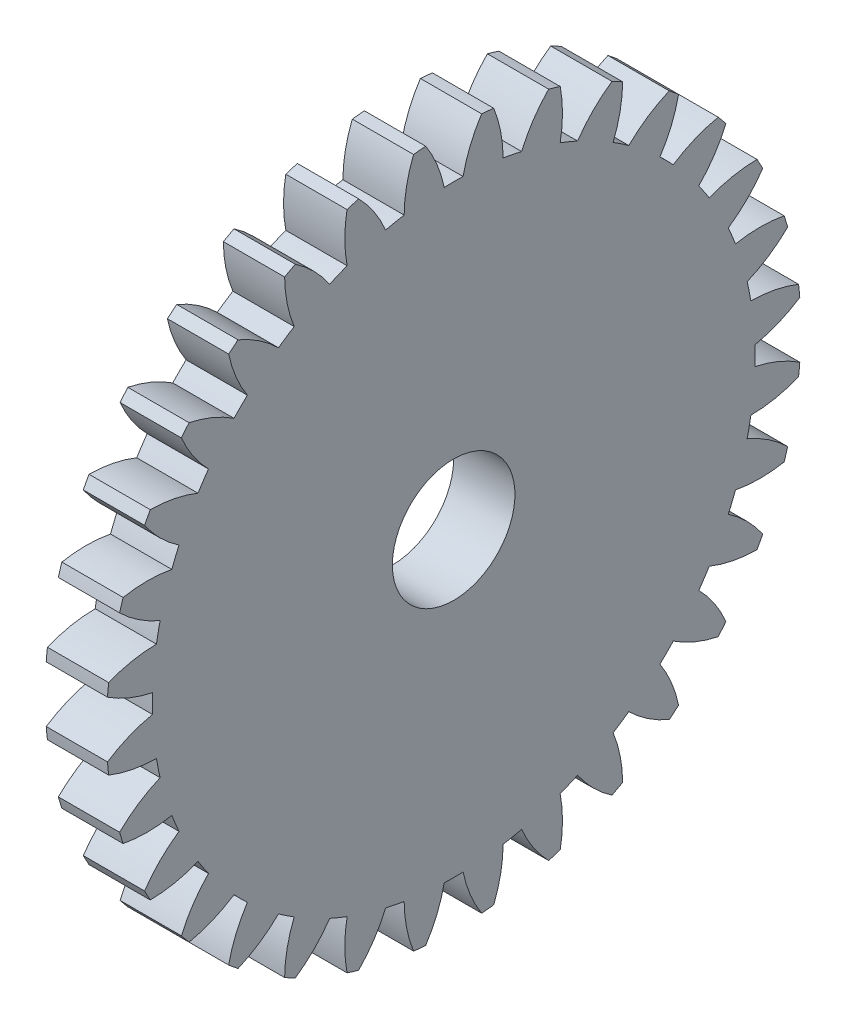
SolidWorks part; units mm, degrees
ref_plane "Plane1" through (0, 0, 0) normal (0, 0, 1) x (1, 0, 0)
ref_plane "Plane2" through (0, 0, 0) normal (0, 1, 0) x (1, 0, 0)
ref_plane "Plane3" through (0, 0, 0) normal (1, 0, 0) x (0, 0, -1)
other "Configuration Table"
sketch "HoldingSke" plane through (0, 0, 0) normal (0, 1, 0) x (1, 0, 0)
  line L0 (0, 0) -> (0.848, -0.5299)
  line L1 (-15, 0) -> (100, 0) construction
  line L2 (0, 0) -> (-2.1039, 2.3779)
  line L3 (0, 0) -> (-11.863, 4.5341)
  line L4 (0, 0) -> (7.3237, 4.5764)
  line L5 (0, 0) -> (-46.8476, -17.4728)
  line L6 (0, 0) -> (-2.4869, -1.6779)
  line L7 (-2.1039, 2.3779) -> (8.6586, 51.2059)
  line L8 (-76.2, 54.61) -> (-75.2, 54.61)
  line L9 (-71.009, 38.7566) -> (-53.1078, 45.2721)
  line L10 (-76.2, 71.12) -> (104.1128, 71.12)
  line L11 (0, 0) -> (-3, 0)
  line L12 (-76.2, 101.6) -> (-76.162, 101.6)
  line L13 (24.9733, 27.94) -> (52.9518, 28.4284)
  line L14 (24.9733, 27.94) -> (24.9743, 27.94)
  line L15 (24.9733, 27.94) -> (100.4006, 29.5858)
  line L16 (-63.627, -1) -> (-12.827, -1)
  circle A0 centre (0, 0) radius 3
  circle A1 centre (0, 0) radius 14.749
  circle A2 centre (0, 0) radius 37.5
  circle A3 centre (0, 0) radius 3
  dimension "MHD" = 29.498
  dimension "Hub_dia" = 75
  dimension "Bore" = 6
  dimension "MBD" = 6
  dimension "Num_teeth" = 32
  dimension "Pitch" = 1
  dimension "Overall_len" = 50
  dimension "Show_teeth" = 32
  dimension "Thickness" = 3
  dimension "OAL" = 50.0001
  dimension "T_dim" = 1
  dimension "Ap" = 20
  dimension "H" = 19.05
  dimension "Pitch_radius" = 180.3128
  dimension "Width" = 3
  dimension "Backlash" = 0.038
  dimension "Addendum_fac" = 1
  dimension "Dedendum_fac" = 1.25
  dimension "Clearance_fac" = 0.25
  dimension "Dedendum_add" = 0.001
  dimension "Module" = 1
sketch "BasProSke" plane through (0, 0, 0) normal (0, 1, 0) x (1, 0, 0)
  line L0 (-10, 0) -> (60, 0) construction
  line L1 (0, 0) -> (0, 17)
  line L2 (0, 0) -> (3, 0)
  line L3 (3, 0) -> (3, 17)
  line L4 (3, 17) -> (0, 17)
  dimension "Thickness" = 3
  dimension "Diameter" = 34
revolve "Base-Revolve" add sketch "BasProSke" angle 360 about L0
sketch "TooCutSke" plane through (0, 0, 0) normal (1, 0, 0) x (0, 0, -1)
  line L1 (0, 0) -> (0, 107) construction
  line L2 (0, 0) -> (-0.8516, 15.9773) construction
  line L3 (0, 0) -> (-3.1334, 31.8138) construction
  line L4 (-0.8516, 15.9773) -> (-1.5667, 15.9069) construction
  arc A0 (0.462, 14.7418) -> (-0.462, 14.7418) centre (0, 0) ccw
  arc A1 (1.3867, 16.9688) -> (-1.3867, 16.9688) centre (0, 0) ccw
  circle A2 centre (0, 0) radius 16 construction
  circle A3 centre (0, 0) radius 15.0351 construction
  arc A4 (-0.462, 14.7418) -> (-1.3867, 16.9688) centre (-6.7293, 13.4451) ccw
  arc A5 (1.3867, 16.9688) -> (0.462, 14.7418) centre (6.7293, 13.4451) ccw
  dimension "Root_dia" = 29.498
  dimension "Overcut_dia" = 34.0508
  dimension "Pitch_dia" = 32
  dimension "Base_dia" = 30.0702
  dimension "Flank_rad" = 6.4
  dimension "Half_ang" = 5.625
  dimension "Half_CT" = 0.7186
extrude "ToothCut" cut sketch "TooCutSke" along normal through all
fillet "Breaks" [suppressed] radius 0.02
fillet "RootFillets" [suppressed] radius 0.251
pattern_circular "TeethCuts" count 32 every 11.25 about axis through (-10, 0, 0) along (1, 0, 0) of "ToothCut", "RootFillets", "Breaks"
sketch "HubNeaOneSke" plane through (0, 0, 0) normal (-1, 0, 0) x (0, 0, 1)
  circle A0 centre (0, 0) radius 14.749
  dimension "Diameter" = 29.498
extrude "HubNearOne" [suppressed] add sketch "HubNeaOneSke" along normal blind 47.0001
sketch "HubNeaBotSke" plane through (0, 0, 0) normal (-1, 0, 0) x (0, 0, 1)
  circle A0 centre (0, 0) radius 14.749
  dimension "Diameter" = 29.498
extrude "HubNearBoth" [suppressed] add sketch "HubNeaBotSke" along normal blind 23.5
ref_plane "FarPln" through (3, 0, 0) normal (1, 0, 0) x (0, 0, -1)
sketch "HubFarSke" plane through (3, 0, 0) normal (1, 0, 0) x (0, 0, -1)
  circle A0 centre (0, 0) radius 14.749
  dimension "Diameter" = 29.498
extrude "HubFar" [suppressed] add sketch "HubFarSke" along normal blind 23.5
sketch "BorSke" plane through (0, 0, 0) normal (1, 0, 0) x (0, 0, -1)
  circle A0 centre (0, 0) radius 3
  dimension "Diameter" = 6
extrude "Bore" cut sketch "BorSke" along normal mid plane 100.0001
sketch "KeySke" plane through (0, 0, 0) normal (1, 0, 0) x (0, 0, -1)
  line L0 (-1, 0) -> (-1, 4)
  line L1 (-1, 4) -> (1, 4)
  line L2 (1, 4) -> (1, 0)
  line L3 (0, 0) -> (0, 34) construction
  line L4 (-1, 0) -> (1, 0)
  dimension "Offset" = 4
  dimension "Width" = 2
extrude "Keyway" [suppressed] cut sketch "KeySke" along normal mid plane 100.0001
pattern_circular "Keyway2" [suppressed] count 2 every 90 about axis through (-10, 0, 0) along (1, 0, 0)
equation "' \"Module@HoldingSke\" = 6.35"
equation "' \"Num_teeth@HoldingSke\" = 12"
equation "' \"Ap@HoldingSke\" =  20"
equation "' \"Ap@HoldingSke\" = 20"
equation "' \"Width@HoldingSke\" = 0.5 * 25.4"
equation "' \"Hub_dia@HoldingSke\"= 1 * 25.4"
equation "' \"Hub_dia@HoldingSke\" = 1 * 25.4"
equation "' \"Overall_len@HoldingSke\" = 1.0 * 25.4"
equation "' \"Bore@HoldingSke\" = 0.75 * 25.4"
equation "' \"T_dim@HoldingSke\" = 0.1 * 25.4"
equation "' \"Width@KeySke\" = 0.25 * 25.4"
equation "' \"Show_teeth@HoldingSke\" = 13"
equation "' \"Backlash@HoldingSke\" = 0.009 * 25.4"
equation "' \"Addendum_fac@HoldingSke\" = 1.0"
equation "' \"Dedendum_fac@HoldingSke\" = 1.25"
equation "' \"Dedendum_add@HoldingSke\" = 0.00005 * 25.4"
equation "' \"Clearance_fac@HoldingSke\" = 0.25"
equation "\"Pitch@HoldingSke\" = 1 / \"Module@HoldingSke\""
equation "\"Overcut_dia@TooCutSke\" = (\"Num_teeth@HoldingSke\" + 2 * \"Addendum_fac@HoldingSke\") / \"Pitch@HoldingSke\" + 0.002 * 25.4"
equation "\"Pitch_dia@TooCutSke\" = \"Num_teeth@HoldingSke\" / \"Pitch@HoldingSke\""
equation "\"Base_dia@TooCutSke\" = \"Num_teeth@HoldingSke\" / \"Pitch@HoldingSke\" * cos((\"Ap@HoldingSke\"  * 3.14159265 / 180))"
equation "\"Root_dia@TooCutSke\" = (\"Num_teeth@HoldingSke\" + 2) / \"Pitch@HoldingSke\" - 2 * (\"Addendum_fac@HoldingSke\" + \"Dedendum_fac@HoldingSke\") / \"Pitch@HoldingSke\" - \"Dedendum_add@HoldingSke\" * 2"
equation "\"Half_ang@TooCutSke\" = 180 / \"Num_teeth@HoldingSke\""
equation "\"Half_CT@TooCutSke\" = \"Num_teeth@HoldingSke\" / \"Pitch@HoldingSke\" * sin((3.14159265 / 2 / \"Num_teeth@HoldingSke\")) / 2 - 7 * \"Backlash@HoldingSke\" / 4"
equation "\"Flank_rad@TooCutSke\" = \"Num_teeth@HoldingSke\" / \"Pitch@HoldingSke\" / 5"
equation "\"Radius@RootFillets\" = \"Clearance_fac@HoldingSke\" / \"Pitch@HoldingSke\" + \"Dedendum_add@HoldingSke\""
equation "\"Break_rad@Breaks\" = 0.02 / \"Pitch@HoldingSke\""
equation "\"Thickness@HoldingSke\" = \"Width@HoldingSke\""
equation "\"OAL@HoldingSke\" = \"Thickness@HoldingSke\""
equation "\"MHD@HoldingSke\" = (\"Num_teeth@HoldingSke\" + 2) / \"Pitch@HoldingSke\" - 2 * (\"Addendum_fac@HoldingSke\" + \"Dedendum_fac@HoldingSke\")  / \"Pitch@HoldingSke\" - \"Dedendum_add@HoldingSke\" * 2"
equation "\"MBD@HoldingSke\" = (\"Num_teeth@HoldingSke\" + 2) / \"Pitch@HoldingSke\" - 2 * (\"Addendum_fac@HoldingSke\" + \"Dedendum_fac@HoldingSke\")  / \"Pitch@HoldingSke\" - \"Dedendum_add@HoldingSke\" * 2 - 0.002 * 25.4"
equation "\"MHD@HoldingSke\" = ((sgn( \"MHD@HoldingSke\" - \"Hub_dia@HoldingSke\" )-1)*( \"MHD@HoldingSke\" - \"Hub_dia@HoldingSke\" ))/-2+ \"Hub_dia@HoldingSke\""
equation "\"MBD@HoldingSke\" = ((sgn( \"MBD@HoldingSke\" - \"Bore@HoldingSke\" )-1)*( \"MBD@HoldingSke\" - \"Bore@HoldingSke\" ))/-2+ \"Bore@HoldingSke\""
equation "\"OAL@HoldingSke\" = ((sgn( \"OAL@HoldingSke\" - \"Overall_len@HoldingSke\" )+1)*( \"OAL@HoldingSke\" - \"Overall_len@HoldingSke\" ))/2 + \"Overall_len@HoldingSke\" + 0.000002 * 25.4"
equation "\"Num_teeth@TeethCuts\" = int( \"Show_teeth@HoldingSke\" ) + 1"
equation "\"Num_teeth@TeethCuts\" = ((sgn( \"Num_teeth@TeethCuts\" - \"Num_teeth@HoldingSke\" )-1)*( \"Num_teeth@TeethCuts\" - \"Num_teeth@HoldingSke\" ))/-2+ \"Num_teeth@HoldingSke\""
equation "\"Num_teeth@TeethCuts\" = ((sgn( \"Num_teeth@TeethCuts\" - 2.0)+1)*( \"Num_teeth@TeethCuts\" - 2.0))/2 +2.0"
equation "\"Angle@TeethCuts\" = 360.0 / \"Num_teeth@HoldingSke\""
equation "\"Diameter@BasProSke\" = (\"Num_teeth@HoldingSke\" + 2 * \"Addendum_fac@HoldingSke\") / \"Pitch@HoldingSke\""
equation "\"Thickness@BasProSke\"  = \"Thickness@HoldingSke\""
equation "' \"Fillet_rad@BasProSke\" =  \"Thickness@HoldingSke\" * 0.05"
equation "' \"Fillet_rad@BasProSke\" = \"Thickness@HoldingSke\" * 0.05"
equation "\"MHD@HoldingSke\" = ((sgn( \"MHD@HoldingSke\" - \"Root_dia@TooCutSke\" )-1)*( \"MHD@HoldingSke\" - \"Root_dia@TooCutSke\" ))/-2+ \"Root_dia@TooCutSke\""
equation "\"Diameter@HubNeaOneSke\" = \"MHD@HoldingSke\""
equation "\"Length@HubNearOne\" = \"OAL@HoldingSke\" - \"Thickness@BasProSke\""
equation "\"Diameter@HubNeaBotSke\" = \"MHD@HoldingSke\""
equation "\"Length@HubNearBoth\" = ( \"OAL@HoldingSke\" - \"Thickness@BasProSke\" ) / 2.0"
equation "\"Thickness@FarPln\" = \"Thickness@BasProSke\""
equation "\"Diameter@HubFarSke\" = \"MHD@HoldingSke\""
equation "\"Length@HubFar\" = ( \"OAL@HoldingSke\" - \"Thickness@BasProSke\" ) / 2.0"
equation "\"Diameter@BorSke\" = \"MBD@HoldingSke\""
equation "\"D1@Bore\" = \"OAL@HoldingSke\" * 2.0"
equation "\"D1@Keyway\" = \"OAL@HoldingSke\" * 2.0"
equation "\"Offset@KeySke\" = \"T_dim@HoldingSke\" + \"MBD@HoldingSke\" / 2.0"
